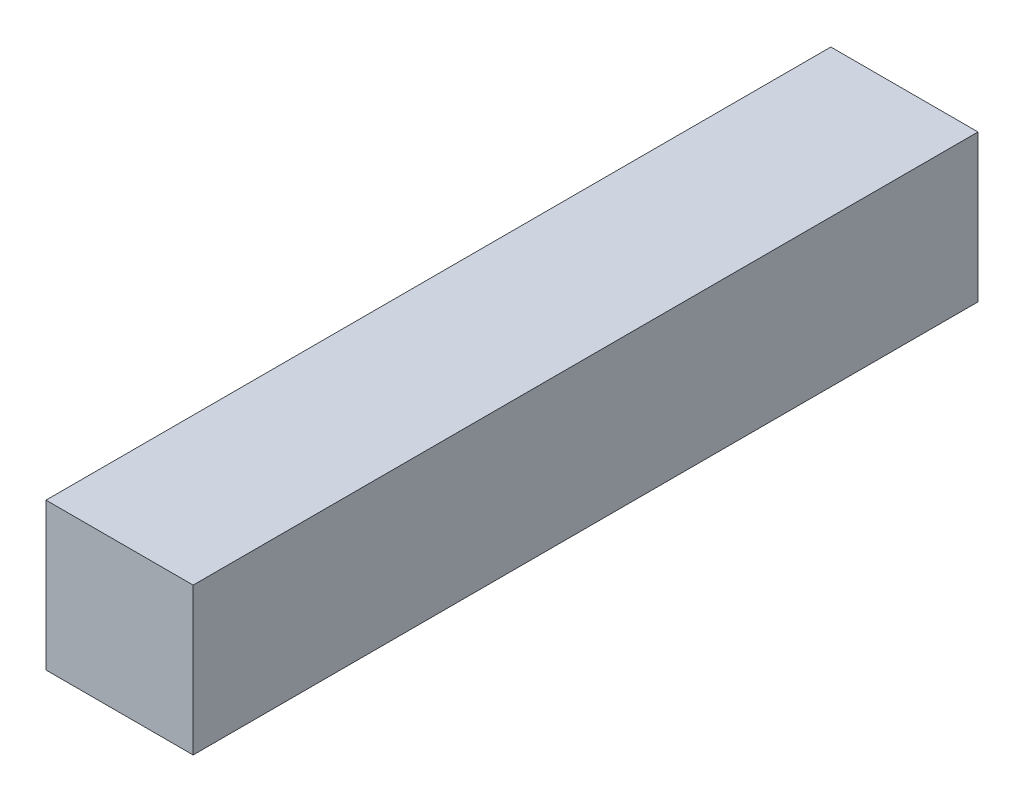
SolidWorks part; units mm, degrees
material "Alloy Steel (SS)"
ref_plane "Front Plane" through (0, 0, 0) normal (0, 0, 1) x (1, 0, 0)
ref_plane "Top Plane" through (0, 0, 0) normal (0, 1, 0) x (1, 0, 0)
ref_plane "Right Plane" through (0, 0, 0) normal (1, 0, 0) x (0, 0, -1)
sketch "Sketch1" plane through (0, 0, 0) normal (0, 0, 1) x (1, 0, 0)
  line L1 (-2.3812, -2.3813) -> (2.3813, -2.3813)
  line L2 (-2.3812, -2.3813) -> (-2.3812, 2.3813)
  line L3 (-2.3812, 2.3813) -> (2.3813, 2.3813)
  line L4 (2.3813, -2.3813) -> (2.3813, 2.3813)
  line L5 (-2.3812, -2.3813) -> (2.3813, 2.3813) construction
  line L6 (-2.3812, 2.3813) -> (2.3813, -2.3813) construction
  point P0 (0, 0)
  dimension "D1" = 4.7625
extrude "Boss-Extrude1" add sketch "Sketch1" along normal blind 25.4
